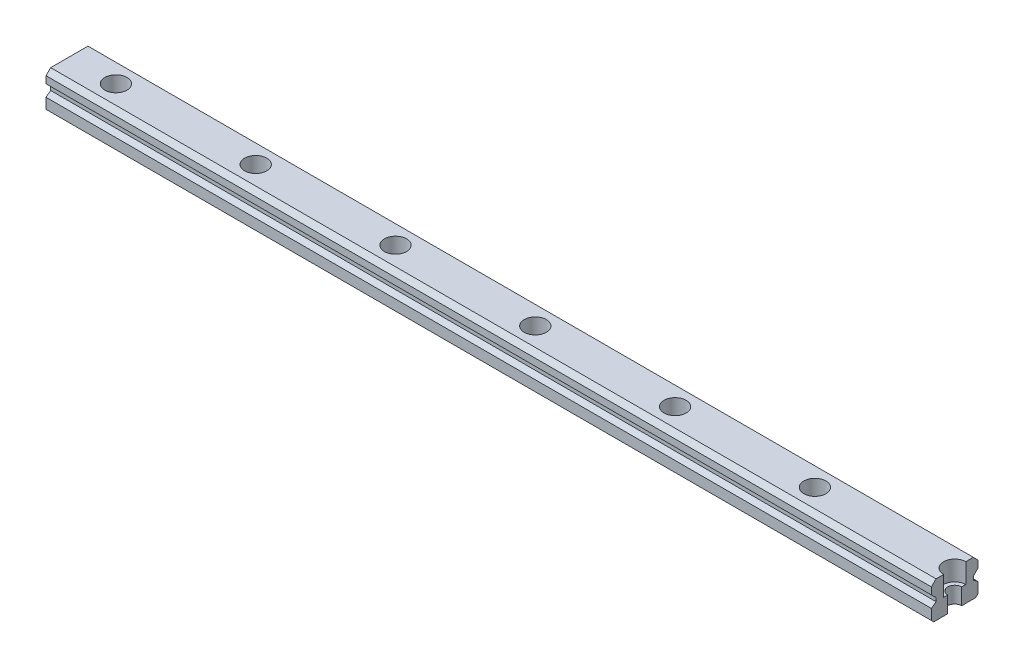
SolidWorks part; units mm, degrees
material "201 Annealed Stainless Steel (SS)"
ref_plane "Front Plane" through (0, 0, 0) normal (0, 0, 1) x (1, 0, 0)
ref_plane "Top Plane" through (0, 0, 0) normal (0, 1, 0) x (1, 0, 0)
ref_plane "Right Plane" through (0, 0, 0) normal (1, 0, 0) x (0, 0, -1)
sketch "Sketch1" plane through (0, 0, 0) normal (1, 0, 0) x (0, 0, -1)
  line L0 (0, 39.5089) -> (0, 0) construction
  line L1 (9, 0) -> (-9, 0)
  line L2 (-9, 0) -> (-10, 1)
  line L3 (-10, 1) -> (-10, 5.5)
  line L4 (-10, 5.5) -> (-8, 7)
  line L5 (-8, 7) -> (-8, 8.5)
  line L6 (-8, 8.5) -> (-10, 10.5)
  line L7 (-10, 10.5) -> (-10, 13.5)
  line L8 (-10, 13.5) -> (-8, 15.5)
  line L9 (-8, 15.5) -> (8, 15.5)
  line L10 (-18.0832, 7.75) -> (13.0406, 7.75) construction
  line L11 (-4.25, 15.5) -> (-4.25, 7) construction
  line L12 (-4.25, 7) -> (-3, 7) construction
  line L13 (-3, 7) -> (-3, 0) construction
  line L14 (4.25, 15.5) -> (4.25, 7) construction
  line L15 (4.25, 7) -> (3, 7) construction
  line L16 (3, 7) -> (3, 0) construction
  line L17 (9, 0) -> (10, 1)
  line L18 (10, 1) -> (10, 5.5)
  line L19 (10, 5.5) -> (8, 7)
  line L20 (8, 7) -> (8, 8.5)
  line L21 (8, 8.5) -> (10, 10.5)
  line L22 (10, 13.5) -> (8, 15.5)
  line L23 (10, 10.5) -> (10, 13.5)
  point P14 (-8, 7.75)
  point P32 (0, 15.5)
  dimension "D1" = 10
  dimension "D2" = 1
  dimension "D3" = 1
  dimension "D4" = 5.5
  dimension "D5" = 7.75
  dimension "D6" = 15.5
  dimension "D7" = 4.25
  dimension "D8" = 3
  dimension "D9" = 8.5
  dimension "D10" = 7
  dimension "D11" = 2
  dimension "D12" = 2
  dimension "D13" = 2
  dimension "D14" = 2
extrude "Boss-Extrude1" add sketch "Sketch1" along normal blind 380
sketch "Sketch2" plane through (0, 15.5, 0) normal (0, 1, 0) x (1, 0, 0)
  line L0 (0, 0) -> (380, 0) construction
  line L1 (0, 8) -> (0, -8) construction
  line L2 (380, 8) -> (380, -8) construction
  circle A0 centre (20, 0) radius 4.75
  dimension "D1" = 9.5
  dimension "D2" = 20
extrude "Cut-Extrude1" cut sketch "Sketch2" against normal blind 8.5
sketch "Sketch3" plane through (0, 7, 0) normal (0, 1, 0) x (1, 0, 0)
  circle A0 centre (20, 0) radius 3
  dimension "D1" = 6
extrude "Cut-Extrude2" cut sketch "Sketch3" against normal through all
pattern_linear "LPattern1" count 33 spacing 60 along (1, 0, 0) of "Cut-Extrude2", "Cut-Extrude1"
